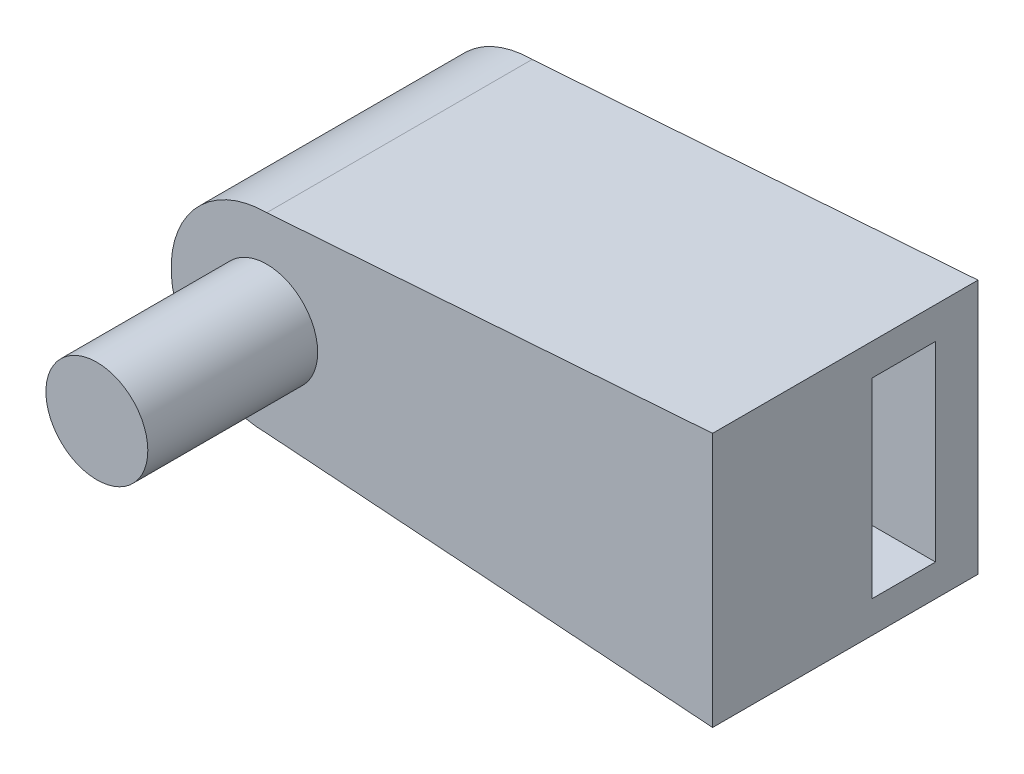
SolidWorks part; units mm, degrees
ref_plane "Front Plane" through (0, 0, 0) normal (1, 0, 0) x (0, 1, 0)
ref_plane "Top Plane" through (0, 0, 0) normal (0, 0, 1) x (0, 1, 0)
ref_plane "Right Plane" through (0, 0, 0) normal (0, 1, 0) x (-1, 0, 0)
sketch "Sketch1" plane through (0, 0, 0) normal (0, 0, 1) x (0, 1, 0)
  line L0 (0, 0) -> (1.5, 0)
  line L1 (10.5, 0) -> (12, 0)
  line L2 (1.5, 21) -> (0, 0)
  line L3 (10.5, 21) -> (12, 0)
  line L5 (1.5, 0) -> (1.5, 5)
  line L6 (10.5, 0) -> (10.5, 5)
  line L9 (1.5, 5) -> (3, 15)
  line L10 (9, 15) -> (10.5, 5)
  arc A0 (10.5, 21) -> (1.5, 21) centre (6, 21) ccw
  arc A1 (9, 15) -> (3, 15) centre (6, 15) ccw
extrude "Boss-Extrude2" add sketch "Sketch1" along normal blind 3 contours L10 L6 L1 L3 A0 L2 L0 L5 L9 A1
sketch "Sketch3" plane through (0, 0, 3) normal (0, 0, 1) x (1, 0, 0)
  line L0 (0, 0) -> (0, 12)
  line L1 (0, 12) -> (-21, 10.5)
  line L2 (0, 0) -> (-21, 1.5)
  arc A0 (-21, 10.5) -> (-21, 1.5) centre (-21, 6) ccw
extrude "Boss-Extrude3" add sketch "Sketch3" along normal blind 7.5
sketch "Sketch4" plane through (0, 0, 0) normal (0, 0, -1) x (1, 0, 0)
  line L0 (0, 0) -> (0, -12)
  line L1 (0, -12) -> (-21, -10.5)
  line L2 (0, 0) -> (-21, -1.5)
  arc A0 (-21, -1.5) -> (-21, -10.5) centre (-21, -6) ccw
extrude "Boss-Extrude4" add sketch "Sketch4" along normal blind 2
sketch "Sketch5" plane through (0, 0, 10.5) normal (0, 0, 1) x (1, 0, 0)
  circle A0 centre (-21, 6) radius 2.4
extrude "Boss-Extrude5" add sketch "Sketch5" along normal blind 8
